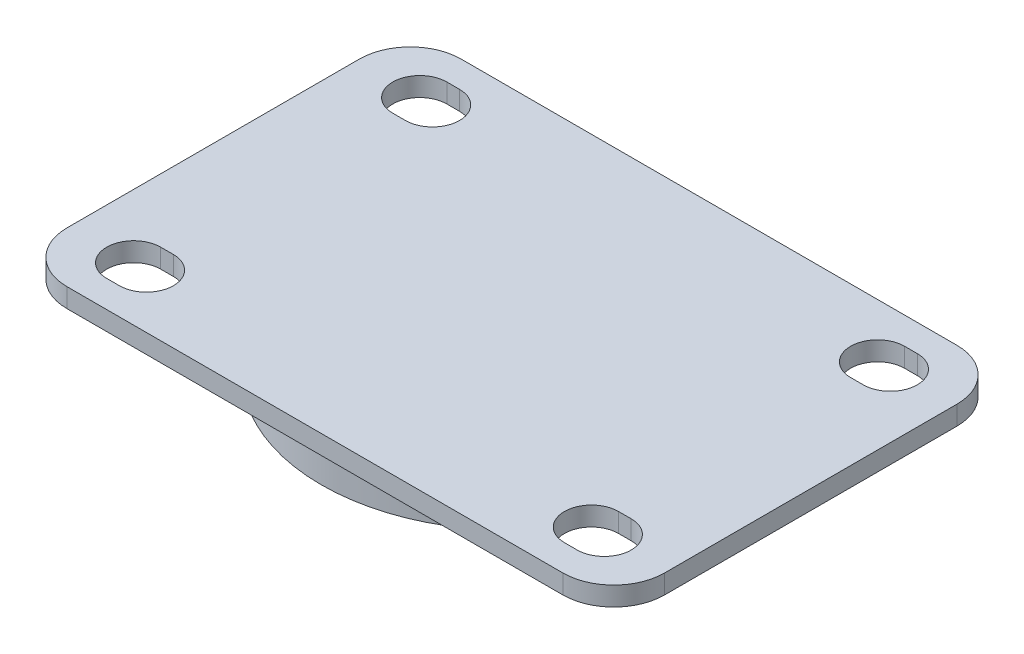
SolidWorks part; units mm, degrees
ref_plane "前视基准面" through (0, 0, 0) normal (0, 0, 1) x (1, 0, 0)
ref_plane "上视基准面" through (0, 0, 0) normal (0, 1, 0) x (1, 0, 0)
ref_plane "右视基准面" through (0, 0, 0) normal (1, 0, 0) x (0, 0, -1)
sketch "草图1" plane through (0, 0, 0) normal (0, 1, 0) x (1, 0, 0)
  line L0 (-37, 22.5) -> (-35, 22.5) construction
  line L1 (47, -31) -> (-47, -31)
  line L2 (47, -31) -> (47, 31)
  line L3 (47, 31) -> (-47, 31)
  line L4 (-47, -31) -> (-47, 31)
  line L5 (47, -31) -> (-47, 31) construction
  line L6 (47, 31) -> (-47, -31) construction
  line L7 (-37, 26.75) -> (-35, 26.75)
  line L8 (-37, 18.25) -> (-35, 18.25)
  line L9 (0, 31) -> (0, -31) construction
  line L10 (47, 0) -> (-47, 0) construction
  line L11 (37, 22.5) -> (35, 22.5) construction
  line L12 (37, 26.75) -> (35, 26.75)
  line L13 (37, 18.25) -> (35, 18.25)
  line L14 (37, -22.5) -> (35, -22.5) construction
  line L15 (37, -26.75) -> (35, -26.75)
  line L16 (37, -18.25) -> (35, -18.25)
  line L17 (-37, -22.5) -> (-35, -22.5) construction
  line L18 (-37, -26.75) -> (-35, -26.75)
  line L19 (-37, -18.25) -> (-35, -18.25)
  arc A0 (-37, 26.75) -> (-37, 18.25) centre (-37, 22.5) ccw
  arc A1 (-35, 18.25) -> (-35, 26.75) centre (-35, 22.5) ccw
  arc A2 (37, 26.75) -> (37, 18.25) centre (37, 22.5) cw
  arc A3 (35, 18.25) -> (35, 26.75) centre (35, 22.5) cw
  arc A4 (37, -26.75) -> (37, -18.25) centre (37, -22.5) ccw
  arc A5 (35, -18.25) -> (35, -26.75) centre (35, -22.5) ccw
  arc A6 (-37, -26.75) -> (-37, -18.25) centre (-37, -22.5) cw
  arc A7 (-35, -18.25) -> (-35, -26.75) centre (-35, -22.5) cw
  point P0 (0, 0)
  point P8 (-36, 22.5)
  point P19 (36, 22.5)
  point P26 (36, -22.5)
  point P33 (-36, -22.5)
  dimension "D4" = 22.5
  dimension "D5" = 4.25
  dimension "D1" = 94
  dimension "D2" = 62
  dimension "D3" = 36
  dimension "D6" = 2
extrude "凸台-拉伸1" add sketch "草图1" along normal blind 3
fillet "圆角1" radius 8 4 edges at (-47, 1.5, 31) (47, 1.5, 31) (47, 1.5, -31) (-47, 1.5, -31)
sketch "草图3" plane through (0, 0, 0) normal (0, 0, 1) x (1, 0, 0)
  line L0 (0, 0) -> (-30, 0) construction
  line L1 (-39, 0) -> (39, 0) construction
  line L2 (-30, 0) -> (-30, -64.5) construction
  line L3 (-30, -64.5) -> (25, 0) construction
  line L4 (25, 0) -> (0, 0) construction
  line L5 (-30, -102) -> (9.091, -102) construction
  circle A0 centre (-30, -64.5) radius 37.5 construction
  dimension "D4" = 75
  dimension "D1" = 30
  dimension "D2" = 25
  dimension "D3" = 64.5
sketch "草图5" plane through (0, 0, 0) normal (1, 0, 0) x (0, 0, -1)
  line L0 (0, 0) -> (-30, 0) construction
  line L1 (-30, 0) -> (-30, -64.5) construction
  line L2 (-30, -64.5) -> (25, 0) construction
  line L3 (25, 0) -> (0, 0) construction
  line L4 (-30, -102) -> (15.7873, -102) construction
  circle A0 centre (-30, -64.5) radius 37.5 construction
  dimension "D4" = 75
  dimension "D1" = 30
  dimension "D2" = 25
  dimension "D3" = 64.5
sketch "草图6" plane through (0, 3, 0) normal (0, 1, 0) x (1, 0, 0)
  line L0 (36, -26.75) -> (36, -18.25) construction
  line L1 (35, -26.75) -> (37, -26.75) construction
  line L2 (37, -18.25) -> (35, -18.25) construction
  line L3 (-36, -18.25) -> (-36, -26.75) construction
  line L4 (-35, -18.25) -> (-37, -18.25) construction
  line L5 (-37, -26.75) -> (-35, -26.75) construction
ref_plane "基准面1" through (36, 0, 0) normal (1, 0, 0) x (0, 0, -1)
ref_plane "基准面2" through (-36, 0, 0) normal (-1, 0, 0) x (0, 0, 1)
sketch "草图7" plane through (0, 0, 0) normal (0, -1, 0) x (1, 0, 0)
  circle A0 centre (0, 0) radius 30
  dimension "D1" = 60
extrude "凸台-拉伸2" add sketch "草图7" along normal blind 5
